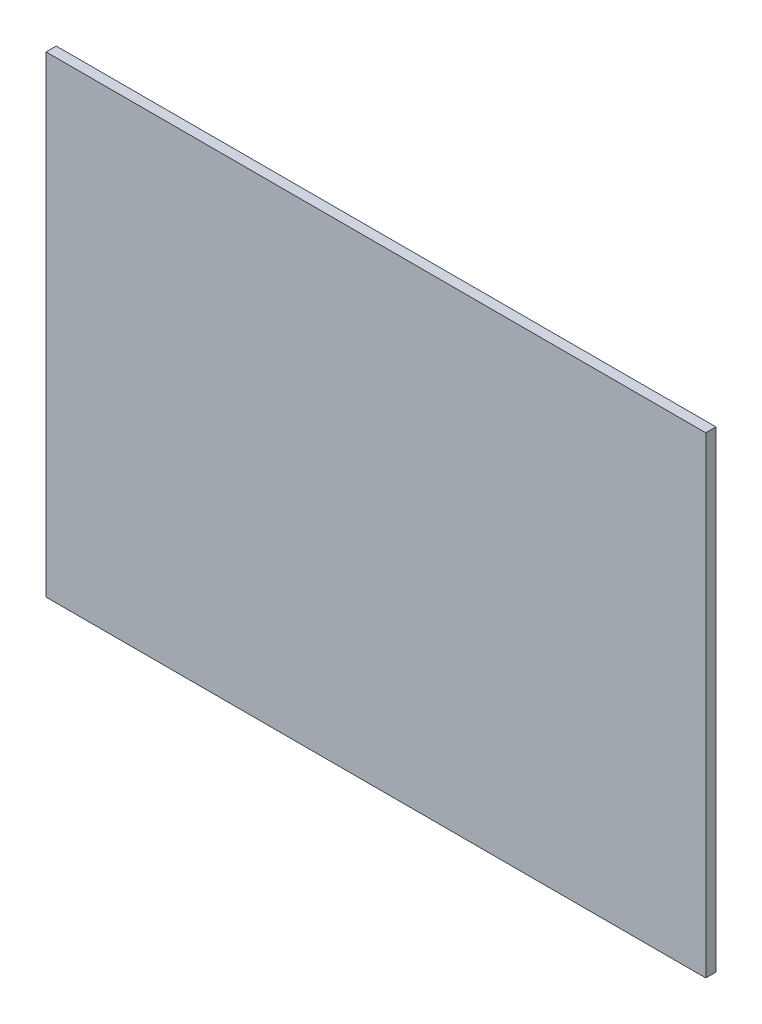
SolidWorks part; units mm, degrees
ref_plane "Plano frontal" through (0, 0, 0) normal (0, 0, 1) x (1, 0, 0)
ref_plane "Plano superior" through (0, 0, 0) normal (0, 1, 0) x (1, 0, 0)
ref_plane "Plano direito" through (0, 0, 0) normal (1, 0, 0) x (0, 0, -1)
sketch "Esboço1" plane through (0, 0, 0) normal (0, 0, 1) x (1, 0, 0)
  line L1 (-463.5714, 251.7857) -> (-353.5714, 251.7857)
  line L2 (-463.5714, 251.7857) -> (-463.5714, 173.0657)
  line L3 (-463.5714, 173.0657) -> (-353.5714, 173.0657)
  line L4 (-353.5714, 251.7857) -> (-353.5714, 173.0657)
  dimension "D1" = 110
  dimension "D2" = 78.72
extrude "Ressalto-extrusão1" add sketch "Esboço1" along normal blind 1.7
sketch3d "3DSketch1"
  point P0 (-419.6772, 226.7613, 1.7)
sketch3d "3DSketch2"
  point P0 (-396.359, 209.896, 1.7)
ref_plane "Plano2" through (0, 0, 1.7) normal (0, 0, 1) x (1, 0, 0)
sketch "Esboço3" plane through (0, 0, 1.7) normal (0, 0, 1) x (1, 0, 0)
  line L1 (-398.5714, 246.7857) -> (-368.5714, 246.7857)
  line L2 (-398.5714, 246.7857) -> (-398.5714, 231.7857)
  line L3 (-398.5714, 231.7857) -> (-368.5714, 231.7857)
  line L4 (-368.5714, 246.7857) -> (-368.5714, 231.7857)
  line L5 (-353.5714, 251.7857) -> (-463.5714, 251.7857) construction
  line L6 (-353.5714, 173.0657) -> (-353.5714, 251.7857) construction
  dimension "D1" = 30
  dimension "D2" = 15
  dimension "D3" = 20
  dimension "25" = 15
